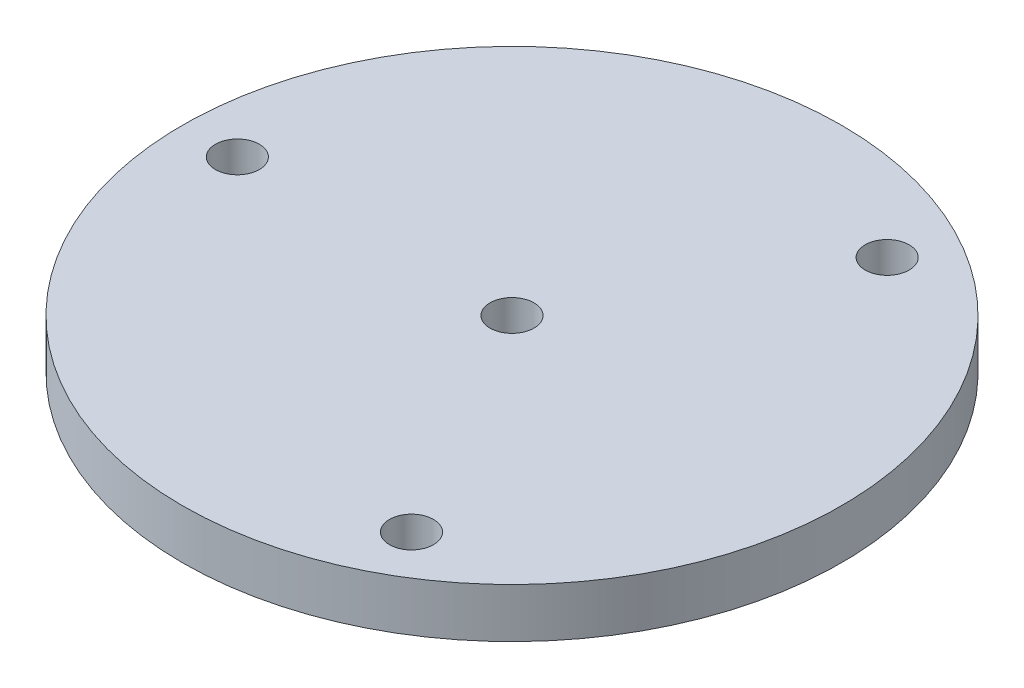
SolidWorks part; units mm, degrees
ref_plane "Front Plane" through (0, 0, 0) normal (0, 0, 1) x (1, 0, 0)
ref_plane "Top Plane" through (0, 0, 0) normal (0, 1, 0) x (1, 0, 0)
ref_plane "Right Plane" through (0, 0, 0) normal (1, 0, 0) x (0, 0, -1)
sketch "Sketch1" plane through (0, 0, 0) normal (0, 1, 0) x (1, 0, 0)
  circle A0 centre (0, 0) radius 60
  circle A1 centre (0, 0) radius 4
  circle A2 centre (-50, 0) radius 4
  circle A3 centre (25, 43.3013) radius 4
  circle A4 centre (25, -43.3013) radius 4
  point P13 (0, 0)
  dimension "D1" = 120
  dimension "D2" = 8
  dimension "D3" = 8
  dimension "D4" = 50
  dimension "D5" = 3
extrude "Boss-Extrude1" add sketch "Sketch1" along normal blind 9
